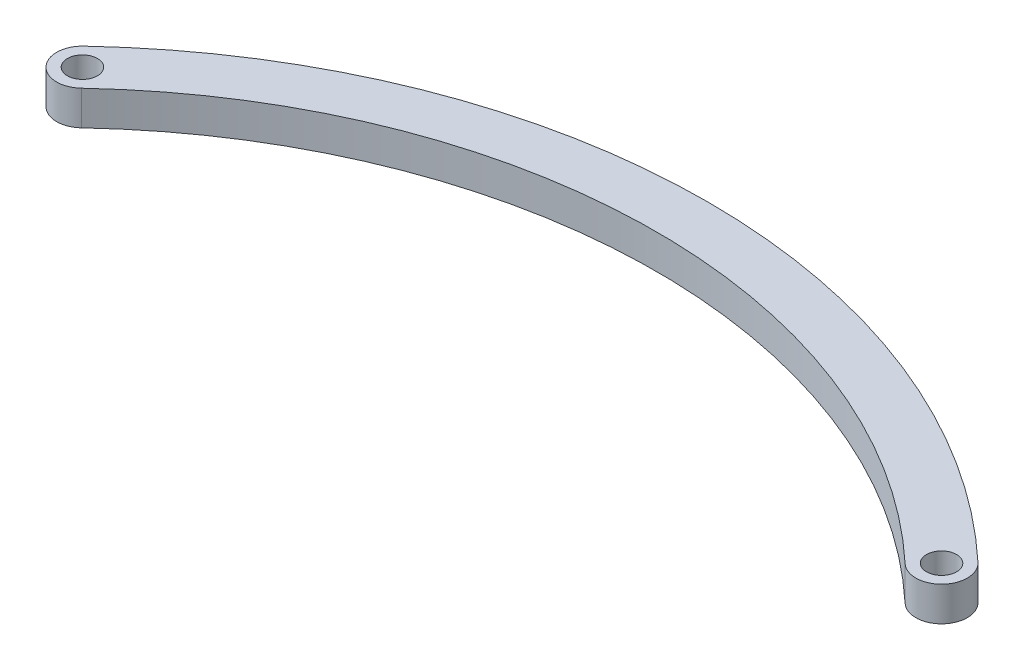
SolidWorks part; units mm, degrees
ref_plane "Front Plane" through (0, 0, 0) normal (0, 0, 1) x (1, 0, 0)
ref_plane "Top Plane" through (0, 0, 0) normal (0, 1, 0) x (1, 0, 0)
ref_plane "Right Plane" through (0, 0, 0) normal (1, 0, 0) x (0, 0, -1)
sketch "Esquisse1" plane through (0, 0, 0) normal (0, 1, 0) x (1, 0, 0)
  line L0 (-50, 0) -> (0, 0) construction
  line L1 (0, 0) -> (50, 0) construction
  circle A0 centre (-50, 0) radius 1.75
  circle A1 centre (50, 0) radius 1.75
  circle A2 centre (-50, 0) radius 3
  circle A3 centre (50, 0) radius 3
  circle A4 centre (0, -53.1883) radius 70
  circle A5 centre (0, -53.1883) radius 76
  dimension "D2" = 3.5
  dimension "D3" = 6
  dimension "D4" = 140
  dimension "D5" = 152
  dimension "D1" = 50
extrude "Boss.-Extru.1" add sketch "Esquisse1" along normal blind 4 contours A3 A5 A2 A4 | A2 A0 | A3 A1
